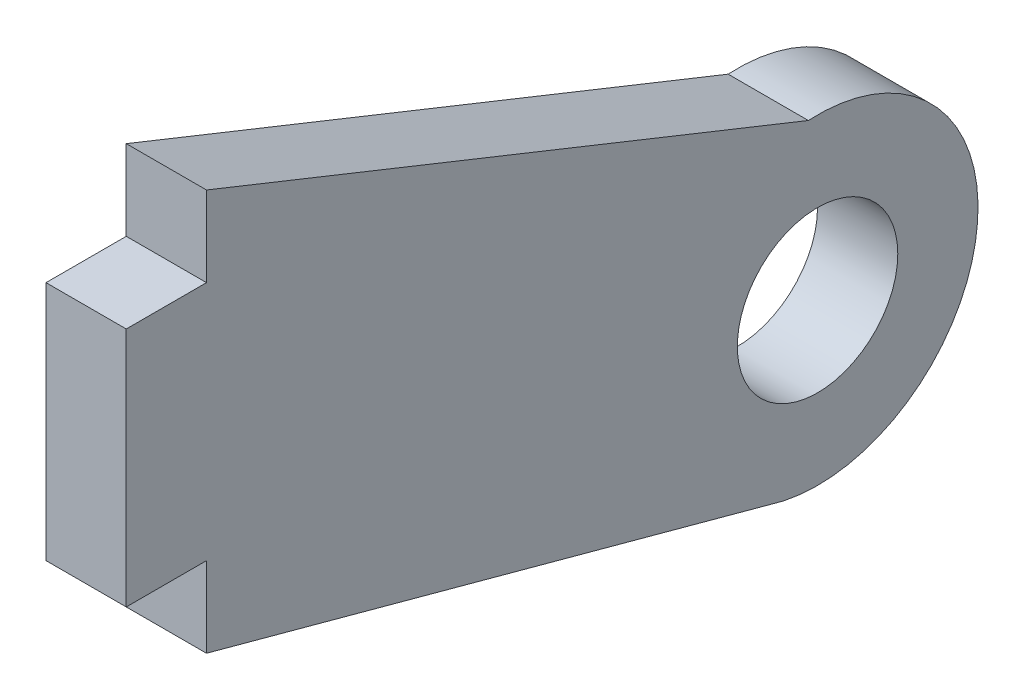
SolidWorks part; units mm, degrees
ref_plane "Front Plane" through (0, 0, 0) normal (0, 0, 1) x (1, 0, 0)
ref_plane "Top Plane" through (0, 0, 0) normal (0, 1, 0) x (1, 0, 0)
ref_plane "Right Plane" through (0, 0, 0) normal (1, 0, 0) x (0, 0, -1)
sketch "Sketch1" plane through (0, 0, 0) normal (1, 0, 0) x (0, 0, -1)
  line L0 (1, -5) -> (1, -3)
  line L1 (-1, 3) -> (1, 3)
  line L2 (-1, 3) -> (-1, -3)
  line L3 (-1, -3) -> (1, -3)
  line L5 (-1, 3) -> (1, -3) construction
  line L6 (-1, -3) -> (1, 3) construction
  line L11 (1, 5) -> (16, -1)
  line L13 (1, 3) -> (1, 5)
  line L14 (1, -5) -> (15, -8.8)
  circle A0 centre (16.2289, -4.9934) radius 2
  arc A1 (15, -8.8) -> (16, -1) centre (16.2289, -4.9934) ccw
  point P0 (0, 0)
  point P8 (15, -8)
  point P9 (15, -8.7851)
  point P12 (1, 0)
  dimension "D3" = 4
  dimension "D4" = 8
  dimension "D1" = 2
  dimension "D2" = 6
  dimension "D5" = 10
  dimension "D6" = 15
  dimension "D7" = 14
  dimension "D8" = 6
  dimension "D9" = 5
  dimension "D10" = 3.8
extrude "Boss-Extrude1" add sketch "Sketch1" along normal blind 2
